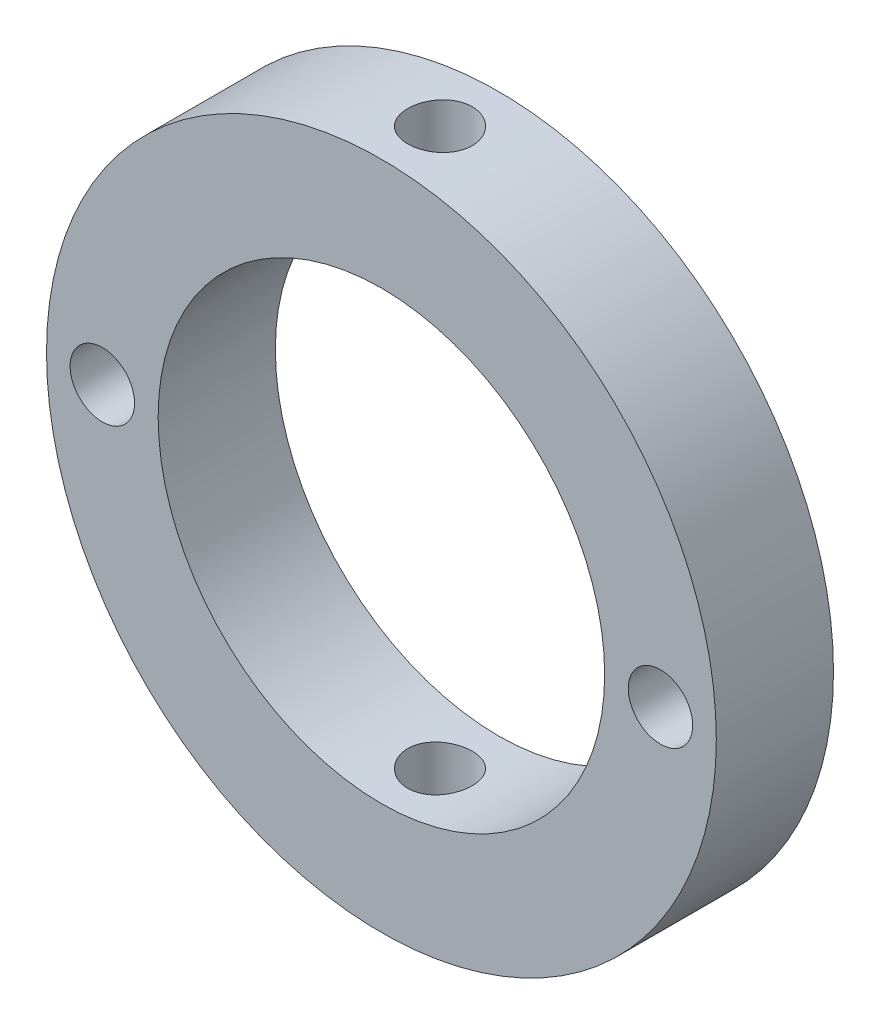
SolidWorks part; units mm, degrees
ref_plane "Front Plane" through (0, 0, 0) normal (0, 0, 1) x (1, 0, 0)
ref_plane "Top Plane" through (0, 0, 0) normal (0, 1, 0) x (1, 0, 0)
ref_plane "Right Plane" through (0, 0, 0) normal (1, 0, 0) x (0, 0, -1)
sketch "Sketch1" plane through (0, 0, 0) normal (0, 0, 1) x (1, 0, 0)
  circle A0 centre (0, 0) radius 28.575
  dimension "D1" = 57.15
extrude "Boss-Extrude1" add sketch "Sketch1" along normal blind 10
sketch "Sketch2" plane through (0, 0, 10) normal (0, 0, 1) x (1, 0, 0)
  circle A0 centre (0, 0) radius 19.05
  dimension "D1" = 38.1
extrude "Cut-Extrude1" cut sketch "Sketch2" against normal through all
ref_plane "Plane1" through (0, 28.575, 0) normal (0, 1, 0) x (1, 0, 0)
sketch "Sketch5" plane through (0, 28.575, 0) normal (0, 1, 0) x (1, 0, 0)
  circle A0 centre (0, -5) radius 2.75
  dimension "D2" = 5.5
  dimension "D1" = 5
extrude "Cut-Extrude2" cut sketch "Sketch5" against normal through all
sketch "Sketch6" plane through (0, 0, 10) normal (0, 0, 1) x (1, 0, 0)
  line L0 (0, 28.575) -> (0, -28.575) construction
  line L1 (5.5, 28.575) -> (-5.5, 28.575) construction
  circle A0 centre (-23.8125, 0) radius 2.75
  circle A1 centre (0, 0) radius 28.575 construction
  circle A2 centre (23.8125, 0) radius 2.75
  point P11 (0, 0)
  point P13 (0, 0)
  point P14 (-23.6975, 0)
  dimension "D2" = 5.5
  dimension "D1" = 23.8125
extrude "Cut-Extrude3" cut sketch "Sketch6" against normal through all
